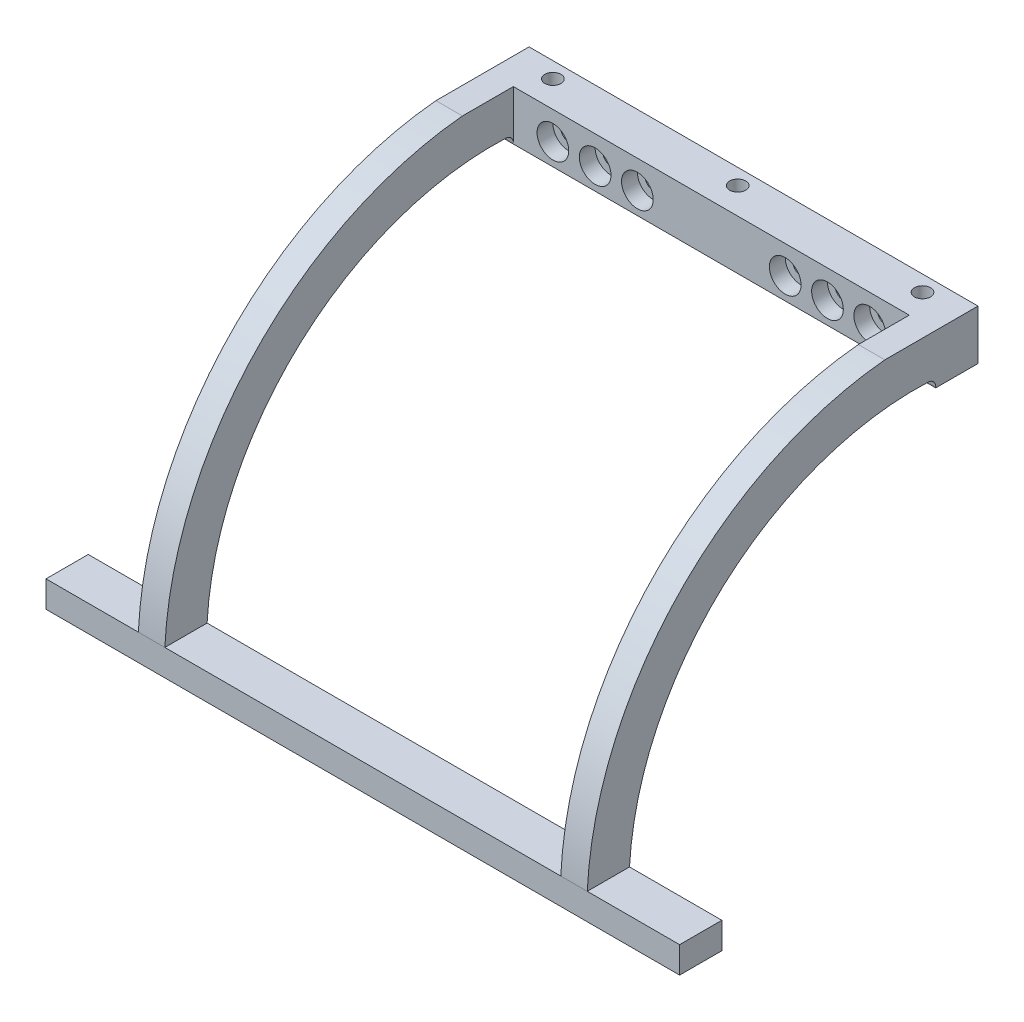
SolidWorks part; units mm, degrees
ref_plane "Front" through (0, 0, 0) normal (0, 0, 1) x (1, 0, 0)
ref_plane "Top" through (0, 0, 0) normal (0, 1, 0) x (1, 0, 0)
ref_plane "Right" through (0, 0, 0) normal (1, 0, 0) x (0, 0, -1)
sketch "草图1" plane through (0, 0, 0) normal (0, 1, 0) x (1, 0, 0)
  line L0 (19.6242, 16.0753) -> (62.3926, 16.0753) construction
  line L9 (60, -4) -> (-60, -4)
  line L10 (60, -4) -> (60, 4)
  line L11 (60, 4) -> (-60, 4)
  line L12 (-60, -4) -> (-60, 4)
  line L13 (60, -4) -> (-60, 4) construction
  line L14 (60, 4) -> (-60, -4) construction
  point P0 (0, 0)
extrude "凸台-拉伸1" add sketch "草图1" along normal blind 5
sketch "草图2" plane through (0, 5, 0) normal (0, 1, 0) x (1, 0, 0)
  line L0 (-60, -4) -> (60, -4) construction
  line L1 (-37.4903, 4) -> (-42.5097, 4)
  line L2 (-37.4903, 4) -> (-37.4903, -4)
  line L3 (-37.4903, -4) -> (-42.5097, -4)
  line L4 (-42.5097, 4) -> (-42.5097, -4)
  line L5 (-37.4903, 4) -> (-42.5097, -4) construction
  line L6 (-37.4903, -4) -> (-42.5097, 4) construction
  point P0 (-40, 0)
ref_plane "基准面2" through (0, 0, -64) normal (0, 0, -1) x (-1, 0, 0)
sketch "草图3" plane through (0, 0, -64) normal (0, 0, -1) x (-1, 0, 0)
  line L2 (-4, 56.25) -> (-4, 63.75)
  line L5 (-4, 56.25) -> (84, 63.75) construction
  line L6 (-4, 63.75) -> (84, 56.25) construction
  point P0 (40, 60)
sketch3d "3D草图2"
  arc A0 (-40, 5, 0) -> (-40, 60, -64) centre (-40, 1.9335, -58.2681) cw
  point P2 (-98.3488, 1.9335, -58.2681)
sweep "扫描2" add profiles "草图2" path "3D草图2"
sketch "草图4" plane through (0, 5, 0) normal (0, 1, 0) x (1, 0, 0)
  line L0 (25.8306, 0) -> (54.8183, 0) construction
pattern_linear "阵列(线性)2" count 2 spacing 80 along (1, 0, 0) of "扫描2"
sketch "草图5" plane through (0, 0, -64) normal (0, 0, -1) x (-1, 0, 0)
  line L0 (-42.5097, 63.9958) -> (-42.5097, 56.0042) construction
  line L1 (-42.5097, 54.5672) -> (42.5097, 54.5672)
  line L2 (-42.5097, 54.5672) -> (-42.5097, 63.9958)
  line L3 (-42.5097, 63.9958) -> (42.5097, 63.9958)
  line L4 (42.5097, 54.5672) -> (42.5097, 63.9958)
  line L5 (-42.5097, 54.5672) -> (42.5097, 63.9958) construction
  line L6 (-42.5097, 63.9958) -> (42.5097, 54.5672) construction
  line L9 (-37.4903, 63.9958) -> (-42.5097, 63.9958) construction
  point P0 (0, 59.2815)
extrude "凸台-拉伸3" add sketch "草图5" along normal blind 6 and the other way blind 2
sketch "草图6" plane through (0, 0, -70) normal (0, 0, -1) x (-1, 0, 0)
  line L0 (0, 63.9958) -> (0, 54.5672) construction
  line L1 (42.5097, 63.9958) -> (-42.5097, 63.9958) construction
  line L2 (-42.5097, 54.5672) -> (42.5097, 54.5672) construction
  line L3 (0, 58.6935) -> (30, 58.6935) construction
  circle A0 centre (30, 58.6935) radius 1.52
extrude "切除-拉伸1" cut sketch "草图6" against normal blind 18
pattern_linear "阵列(线性)3" count 3 spacing 8 along (1, 0, 0) of "切除-拉伸1"
ref_plane "基准面3" through (0, 0, 0) normal (1, 0, 0) x (0, 0, -1)
mirror "镜向1" about plane through (0, 0, 0) normal (1, 0, 0) of "阵列(线性)3", "切除-拉伸1"
sketch "草图7" plane through (0, 54.5672, 0) normal (0, -1, 0) x (-1, 0, 0)
  line L0 (0, 70) -> (0, 64) construction
  line L1 (-42.5097, 70) -> (42.5097, 70) construction
  line L2 (-4, 64) -> (84, 64) construction
  line L3 (35, 67) -> (0, 67) construction
  circle A0 centre (0, 67) radius 1.52
  circle A1 centre (35, 67) radius 1.52
  circle A2 centre (-35, 67) radius 1.52
  point P12 (0, 67)
extrude "切除-拉伸2" cut sketch "草图7" against normal blind 15
sketch "草图8" plane through (0, 63.9958, 0) normal (0, 1, 0) x (1, 0, 0)
  line L1 (-66.1569, 72.8939) -> (70.5329, 72.8939)
  line L2 (-66.1569, 72.8939) -> (-66.1569, 32.0551)
  line L3 (-66.1569, 32.0551) -> (70.5329, 32.0551)
  line L4 (70.5329, 72.8939) -> (70.5329, 32.0551)
  line L5 (-66.1569, 72.8939) -> (70.5329, 32.0551) construction
  line L6 (-66.1569, 32.0551) -> (70.5329, 72.8939) construction
  point P0 (2.188, 52.4745)
extrude "切除-拉伸3" cut sketch "草图8" along normal blind 8
sketch "草图9" plane through (-60, 0, 0) normal (-1, 0, 0) x (0, 0, 1)
  circle A0 centre (0, 2.5) radius 1.2
sketch "草图10" plane through (0, 0, -62) normal (0, 0, 1) x (1, 0, 0)
  line L1 (0, 54.5672) -> (0, 63.9645) construction
  line L2 (42.5097, 54.5672) -> (-42.5097, 54.5672) construction
  circle A0 centre (30, 58.6935) radius 3
  circle A1 centre (22, 58.6935) radius 3
  circle A2 centre (14, 58.6935) radius 3
  circle A4 centre (-30, 58.6935) radius 3
  circle A5 centre (-22, 58.6935) radius 3
  circle A6 centre (-14, 58.6935) radius 3
extrude "切除-拉伸5" cut sketch "草图10" against normal blind 3
fillet "圆角1" radius 1.5 1 edges at (40, 56.1599, -62)
fillet "圆角2" radius 1.5 1 edges at (-40, 56.1599, -62)
